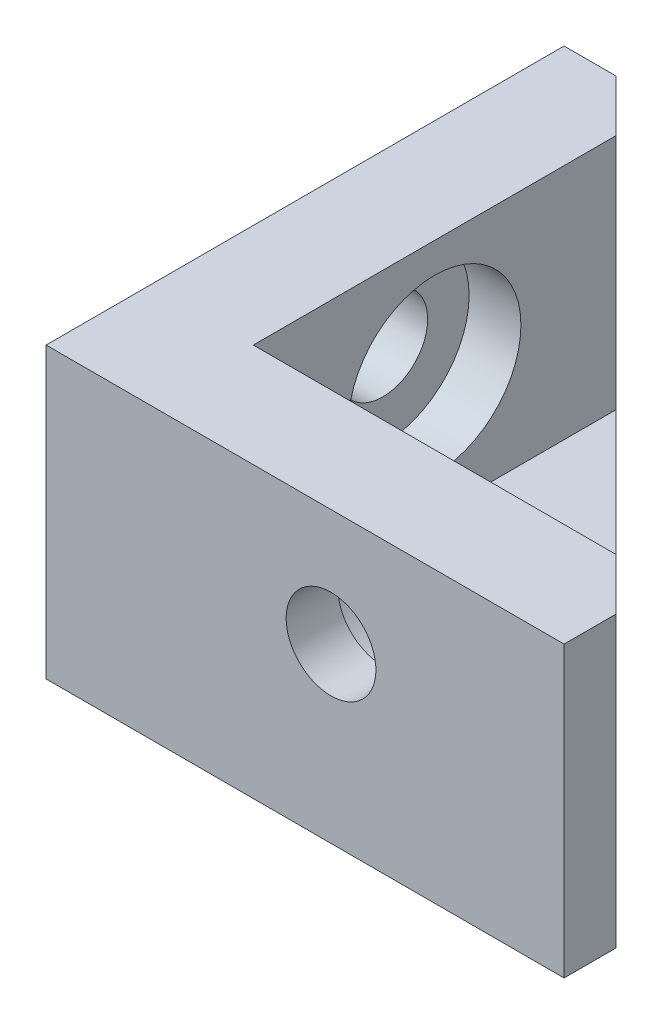
SolidWorks part; units mm, degrees
ref_plane "前视基准面" through (0, 0, 0) normal (0, 0, 1) x (1, 0, 0)
ref_plane "上视基准面" through (0, 0, 0) normal (0, 1, 0) x (1, 0, 0)
ref_plane "右视基准面" through (0, 0, 0) normal (1, 0, 0) x (0, 0, -1)
other "Configuration Table"
sketch "草图1" plane through (0, 0, 0) normal (0, 1, 0) x (1, 0, 0)
  line L0 (0, 0) -> (0, 30)
  line L1 (0, 0) -> (30, 0)
  line L2 (0, 30) -> (3, 30)
  line L3 (30, 0) -> (30, 3)
  line L4 (3, 30) -> (3, 3)
  line L5 (3, 3) -> (30, 3)
extrude "凸台-拉伸1" add sketch "草图1" along normal blind 20
sketch "草图2" plane through (0, 0, 0) normal (0, -1, 0) x (1, 0, 0)
  line L0 (3, -30) -> (30, -3)
  line L1 (30, -3) -> (3, -3)
  line L2 (3, -3) -> (3, -30)
extrude "凸台-拉伸2" add sketch "草图2" against normal blind 2
sketch "草图5" plane through (0, 0, -3) normal (0, 0, -1) x (-1, 0, 0)
  line L0 (-30, 20) -> (-3, 0)
  circle A0 centre (-16.5, 10) radius 2.6
extrude "切除-拉伸2" cut sketch "草图5" against normal blind 30 contours L0 A0 | L0 A0
sketch "草图7" plane through (3, 0, 0) normal (1, 0, 0) x (0, 0, -1)
  line L0 (3, 20) -> (30, 0)
  circle A0 centre (16.5, 10) radius 2.6
extrude "切除-拉伸3" cut sketch "草图7" against normal blind 30 contours L0 A0 | L0 A0
sketch "草图8" plane through (0, 0, -3) normal (0, 0, -1) x (-1, 0, 0)
  line L1 (-30, 20) -> (-3, 20)
  line L2 (-30, 20) -> (-30, 2)
  line L3 (-30, 2) -> (-3, 2)
  line L4 (-3, 20) -> (-3, 2)
  circle A0 centre (-16.5, 10) radius 5
extrude "凸台-拉伸3" add sketch "草图8" along normal blind 3
sketch "草图9" plane through (3, 0, 0) normal (1, 0, 0) x (0, 0, -1)
  line L1 (6, 20) -> (30, 20)
  line L2 (6, 20) -> (6, 2)
  line L3 (6, 2) -> (30, 2)
  line L4 (30, 20) -> (30, 2)
  circle A0 centre (16.5, 10) radius 5
extrude "凸台-拉伸4" add sketch "草图9" along normal blind 3
sketch "草图10" plane through (0, 2, 0) normal (0, -1, 0) x (1, 0, 0)
  line L0 (3, -30) -> (6, -27)
  line L1 (6, -27) -> (6, -30)
  line L2 (6, -30) -> (3, -30)
  line L3 (27, -6) -> (30, -3)
  line L4 (30, -3) -> (30, -6)
  line L5 (30, -6) -> (27, -6)
extrude "切除-拉伸4" cut sketch "草图10" against normal blind 30
sketch "草图12" plane through (30, 0, 0) normal (1, 0, 0) x (0, 0, -1)
  line L0 (30, 20) -> (30, 0) construction
  line L1 (0, 20) -> (30, 20)
  line L2 (0, 20) -> (0, 16.75)
  line L3 (0, 16.75) -> (30, 16.75)
  line L4 (30, 20) -> (30, 16.75)
extrude "切除-拉伸5" cut sketch "草图12" against normal blind 30
sketch "草图13" plane through (0, 0, 0) normal (0, -1, 0) x (1, 0, 0)
  line L0 (3, -30) -> (3, -3)
  line L1 (30, -3) -> (3, -3)
  line L2 (3, -30) -> (30, -3)
extrude "凸台-拉伸5" add sketch "草图13" against normal blind 3
